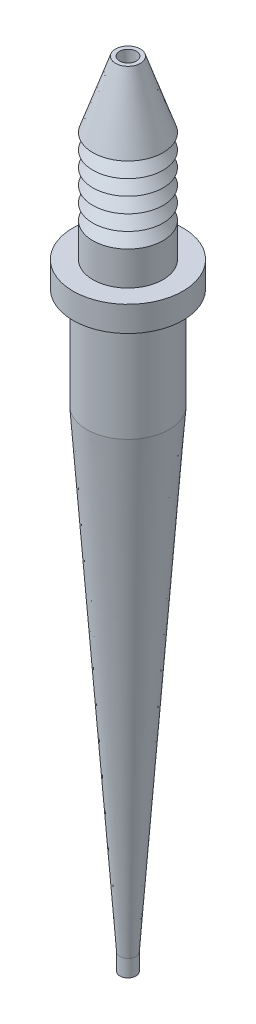
SolidWorks part; units mm, degrees
ref_plane "Front Plane" through (0, 0, 0) normal (0, 0, 1) x (1, 0, 0)
ref_plane "Top Plane" through (0, 0, 0) normal (0, 1, 0) x (1, 0, 0)
ref_plane "Right Plane" through (0, 0, 0) normal (1, 0, 0) x (0, 0, -1)
sketch "Sketch1" plane through (0, 0, 0) normal (0, 0, 1) x (1, 0, 0)
  line L0 (0, 103.0145) -> (0, -9.8367) construction
  line L1 (0.95, -9.3367) -> (0.95, -7.3367)
  line L2 (6.5, 63.6633) -> (6.5, 60.6633)
  line L3 (6.5, 60.6633) -> (4.875, 60.6633)
  line L4 (6.5, 63.6633) -> (4.15, 63.6633)
  line L5 (4.15, 63.6633) -> (4.15, 67.6633)
  line L7 (4.15, 67.6633) -> (2.6484, 69.4685)
  line L8 (2.6484, 69.4685) -> (4.15, 69.4685)
  line L9 (4.15, 69.4685) -> (2.6484, 71.2738)
  line L10 (2.6484, 71.2738) -> (4.15, 71.2738)
  line L11 (4.15, 71.2738) -> (2.6484, 73.079)
  line L12 (2.6484, 73.079) -> (4.15, 73.079)
  line L13 (4.15, 73.079) -> (2.6484, 74.8842)
  line L14 (2.6484, 74.8842) -> (4.15, 74.8842)
  line L15 (4.15, 74.8842) -> (2.6484, 76.6895)
  line L16 (2.6484, 76.6895) -> (4.15, 76.6895)
  line L18 (1, 84.5108) -> (1, 68.9685)
  line L20 (0.95, -9.3367) -> (0.575, -9.3367)
  line L21 (0.575, -9.3367) -> (0.575, -8.3367)
  line L22 (0.575, -8.3367) -> (0.275, -8.3367)
  line L25 (1, 84.5108) -> (1.4742, 84.5108)
  line L26 (1.4742, 84.5108) -> (4.15, 76.6895)
  line L27 (4.875, 60.6633) -> (4.875, 48.6633)
  line L28 (4.875, 48.6633) -> (0.95, -7.3367)
  line L29 (0.275, -8.3367) -> (0.275, -7.0027)
  line L30 (0.275, -7.0027) -> (2, 60.6633)
  line L31 (2, 60.6633) -> (2, 63.6633)
  line L32 (2, 63.6633) -> (1, 68.9685)
  dimension "D2" = 2
  dimension "D3" = 68
  dimension "D4" = 13
  dimension "D5" = 3
  dimension "D6" = 8.3
  dimension "D7" = 4
  dimension "D8" = 9.75
  dimension "D9" = 2
  dimension "D10" = 1.15
  dimension "D11" = 1
  dimension "D12" = 0.3
  dimension "D13" = 12
  dimension "D14" = 4
revolve "Revolve1" add sketch "Sketch1" angle 360 about L0
chamfer "Chamfer1" distance 0.2 angle 45 1 edges at (0, -9.3367, 0.575)
